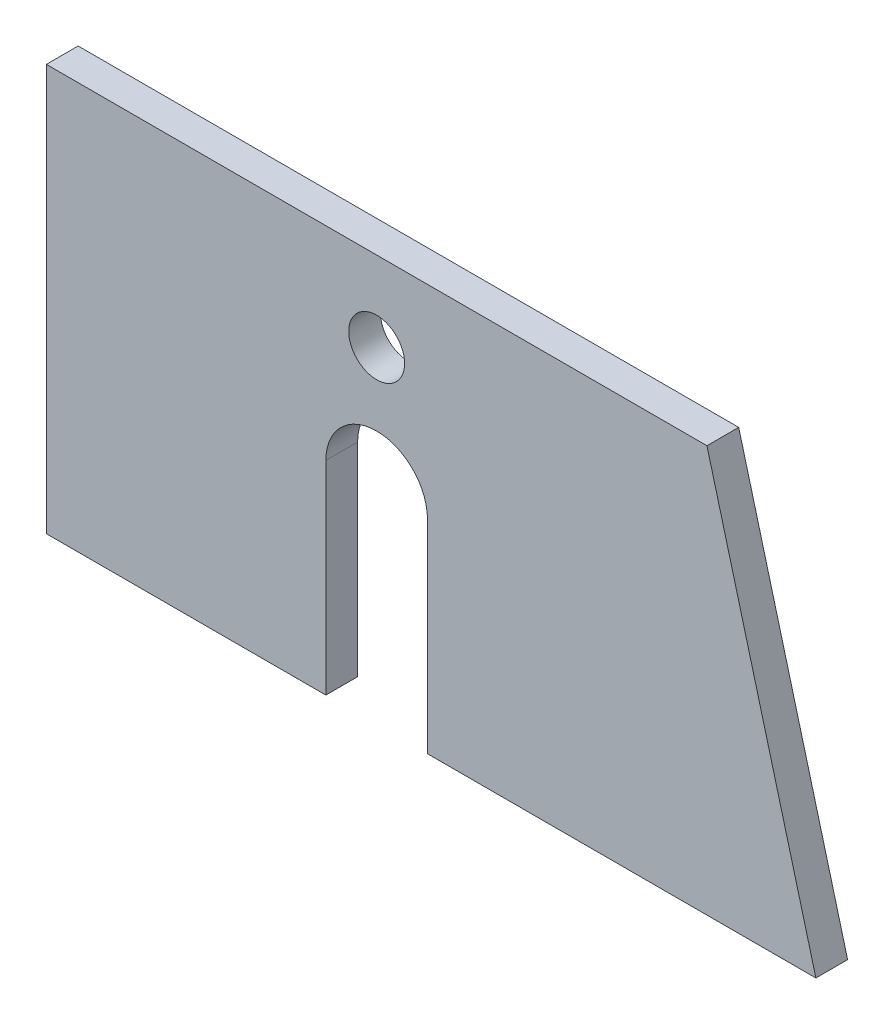
SolidWorks part; units mm, degrees
material "Plain Carbon Steel"
ref_plane "Front Plane" through (0, 0, 0) normal (0, 0, 1) x (1, 0, 0)
ref_plane "Top Plane" through (0, 0, 0) normal (0, 1, 0) x (1, 0, 0)
ref_plane "Right Plane" through (0, 0, 0) normal (1, 0, 0) x (0, 0, -1)
sketch "Sketch1" plane through (0, 0, 0) normal (0, 0, 1) x (1, 0, 0)
  line L1 (-32.5, 20) -> (32.5, 20)
  line L2 (-32.5, 20) -> (-32.5, -20)
  line L3 (-32.5, -20) -> (-5, -20)
  line L6 (5, -20) -> (43.218, -20)
  line L7 (-5, 0) -> (-5, -20)
  line L8 (5, 0) -> (5, -20)
  line L9 (32.5, 20) -> (43.218, -20)
  arc A0 (5, 0) -> (-5, 0) centre (0, 0) ccw
  circle A1 centre (0, 0) radius 5 construction
  circle A2 centre (0, 12.125) radius 2.75
  point P1 (0, 20)
  point P9 (43.1974, -19.9232)
  dimension "D1" = 10
  dimension "D5" = 5.5
  dimension "D2" = 65
  dimension "D3" = 20
  dimension "D4" = 20
  dimension "D6" = 12.125
  dimension "D7" = 75
extrude "Boss-Extrude1" add sketch "Sketch1" along normal blind 3.125
